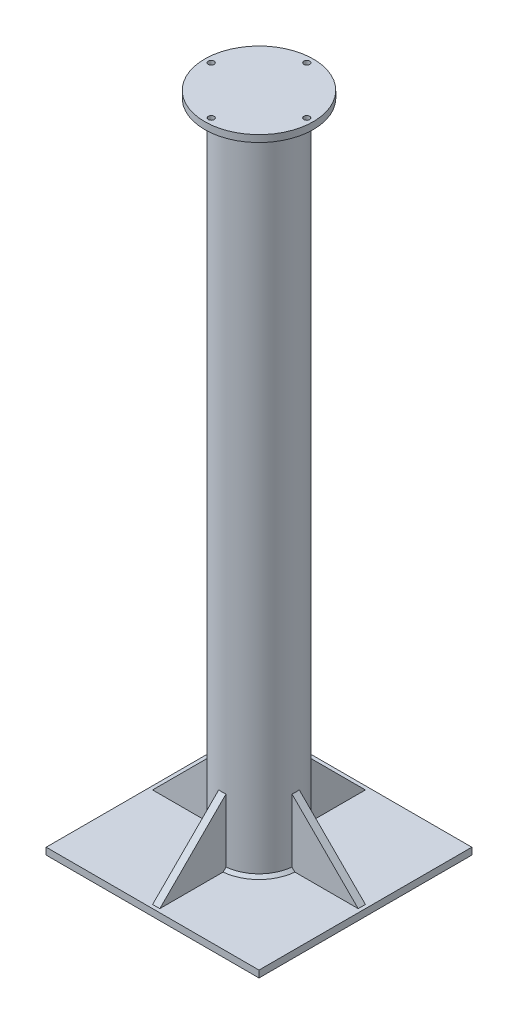
SolidWorks part; units mm, degrees
ref_plane "Alzado" through (0, 0, 0) normal (0, 0, 1) x (1, 0, 0)
ref_plane "Planta" through (0, 0, 0) normal (0, 1, 0) x (1, 0, 0)
ref_plane "Vista lateral" through (0, 0, 0) normal (1, 0, 0) x (0, 0, -1)
sketch "Croquis1" plane through (0, 0, 0) normal (0, 1, 0) x (1, 0, 0)
  circle A0 centre (0, 0) radius 50.8
  dimension "D1" = 101.6
extrude "Saliente-Extruir1" add sketch "Croquis1" along normal mid plane 896
sketch "Croquis2" plane through (0, -448, 0) normal (0, -1, 0) x (1, 0, 0)
  line L1 (-147, 147) -> (147, 147)
  line L2 (-147, 147) -> (-147, -147)
  line L3 (-147, -147) -> (147, -147)
  line L4 (147, 147) -> (147, -147)
  line L5 (-147, 147) -> (147, -147) construction
  line L6 (-147, -147) -> (147, 147) construction
  point P0 (0, 0)
  dimension "D1" = 294
  dimension "D2" = 294
extrude "Saliente-Extruir2" add sketch "Croquis2" along normal blind 9.5
sketch "Croquis3" plane through (0, 448, 0) normal (0, 1, 0) x (1, 0, 0)
  circle A0 centre (0, 0) radius 75
  dimension "D1" = 150
extrude "Saliente-Extruir3" add sketch "Croquis3" along normal blind 9.5
sketch "Croquis4" plane through (0, 457.5, 0) normal (0, 1, 0) x (1, 0, 0)
  circle A0 centre (0, 66) radius 4
  dimension "D1" = 8
  dimension "D2" = 66
extrude "Cortar-Extruir1" cut sketch "Croquis4" against normal up to next
pattern_circular "MatrizC1" count 4 over 360 about axis through (0, 0, 0) along (0, 1, 0) of "Cortar-Extruir1"
chamfer "Chaflán1" distance 4 angle 45 1 edges at (0, -448, -50.8)
sketch "Croquis5" plane through (0, 0, 0) normal (0, 0, 1) x (1, 0, 0)
  line L0 (-142, -448) -> (-50.8, -356.8)
  line L1 (147, -448) -> (-147, -448) construction
  line L2 (-50.8, 448) -> (-50.8, -444) construction
  dimension "D1" = 128.9763
  dimension "D3" = 5
rib "Nervio2" sketch "Croquis5" sketch "Croquis5" thickness 10 extrusion direction parallel to sketch draft on no parameters "D1"=10
pattern_circular "MatrizC2" count 4 over 360 about axis through (0, 0, 0) along (0, 1, 0) of "Nervio2"
